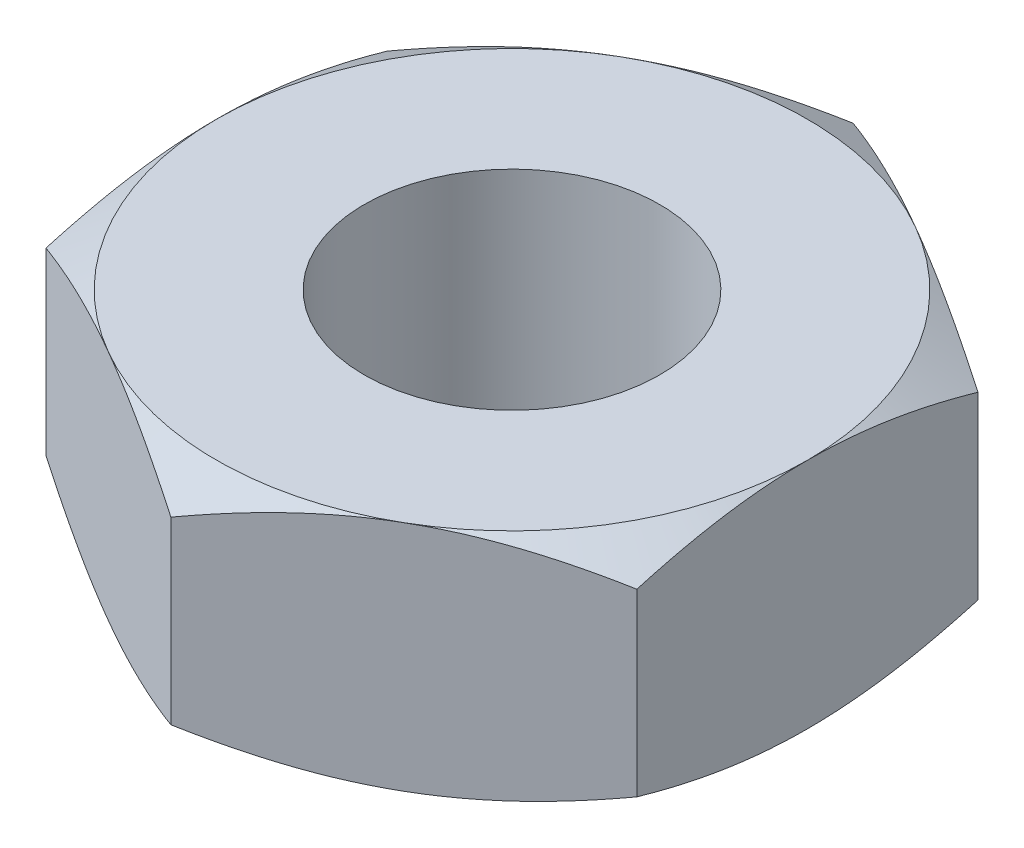
SolidWorks part; units mm, degrees
ref_plane "Front Plane" through (0, 0, 0) normal (0, 0, 1) x (1, 0, 0)
ref_plane "Top Plane" through (0, 0, 0) normal (0, 1, 0) x (1, 0, 0)
ref_plane "Right Plane" through (0, 0, 0) normal (1, 0, 0) x (0, 0, -1)
sketch "Sketch2" plane through (0, 0, 0) normal (0, 1, 0) x (1, 0, 0)
  line L1 (0, -14.6647) -> (12.7, -7.3323)
  line L2 (12.7, -7.3323) -> (12.7, 7.3323)
  line L3 (12.7, 7.3323) -> (0, 14.6647)
  line L4 (0, 14.6647) -> (-12.7, 7.3323)
  line L5 (-12.7, 7.3323) -> (-12.7, -7.3323)
  line L6 (-12.7, -7.3323) -> (0, -14.6647)
  circle A0 centre (0, 0) radius 12.7 construction
  dimension "D1" = 25.4
extrude "Boss-Extrude2" add sketch "Sketch2" along normal mid plane 10
sketch "Sketch6" plane through (0, 5, 0) normal (0, 1, 0) x (1, 0, 0)
  circle A0 centre (0, 0) radius 6.35
  dimension "D1" = 12.7
extrude "Cut-Extrude3" cut sketch "Sketch6" against normal through all
cosmetic thread "Cosmetic Thread2" parameters "D1"=10, "D2"=14.2875
sketch "Sketch7" plane through (0, 5, 0) normal (0, 1, 0) x (1, 0, 0)
  circle A0 centre (0, 0) radius 12.7
extrude "Cut-Extrude4" cut sketch "Sketch7" against normal through all draft 60 flip side to cut
mirror "Mirror3" about plane through (0, 0, 0) normal (0, 1, 0) of "Cut-Extrude4"
